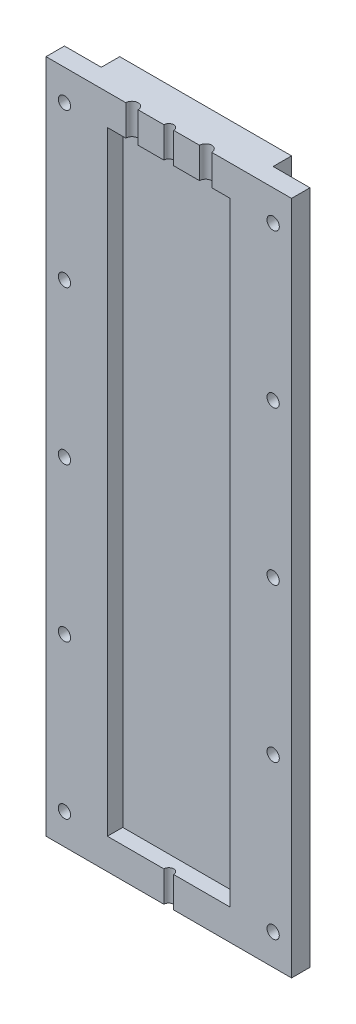
SolidWorks part; units mm, degrees
ref_plane "Front Plane" through (0, 0, 0) normal (0, 0, 1) x (1, 0, 0)
ref_plane "Top Plane" through (0, 0, 0) normal (0, 1, 0) x (1, 0, 0)
ref_plane "Right Plane" through (0, 0, 0) normal (1, 0, 0) x (0, 0, -1)
sketch "Sketch1" plane through (0, 0, 0) normal (0, 1, 0) x (1, 0, 0)
  line L1 (0, 0) -> (0, 6) construction
  line L6 (14, 0) -> (-14, 0)
  line L7 (14, 0) -> (14, 6)
  line L8 (14, 6) -> (-14, 6)
  line L9 (-14, 0) -> (-14, 6)
  dimension "D1" = 28
  dimension "D2" = 6
extrude "Boss-Extrude1" add sketch "Sketch1" along normal blind 105
sketch "Sketch2" plane through (0, 105, 0) normal (0, 1, 0) x (1, 0, 0)
  line L1 (-10, -2.5) -> (10, -2.5)
  line L2 (-10, -2.5) -> (-10, 2.5)
  line L3 (-10, 2.5) -> (10, 2.5)
  line L4 (10, -2.5) -> (10, 2.5)
  line L5 (-10, -2.5) -> (10, 2.5) construction
  line L6 (-10, 2.5) -> (10, -2.5) construction
  point P0 (0, 0)
  dimension "D1" = 5
  dimension "D2" = 20
extrude "Cut-Extrude1" cut sketch "Sketch2" against normal blind 100
sketch "Sketch3" plane through (0, 105, 0) normal (0, 1, 0) x (1, 0, 0)
  line L1 (14, 0) -> (20, 0)
  line L2 (14, 0) -> (14, 3)
  line L3 (14, 3) -> (20, 3)
  line L4 (20, 0) -> (20, 3)
  line L5 (0, 0) -> (0, 15) construction
  line L6 (-14, 3) -> (-20, 3)
  line L7 (-20, 0) -> (-20, 3)
  line L8 (-14, 0) -> (-20, 0)
  line L9 (-14, 0) -> (-14, 3)
  dimension "D1" = 3
  dimension "D2" = 6
extrude "Boss-Extrude2" add sketch "Sketch3" against normal blind 105
sketch "Sketch5" plane through (0, 105, 0) normal (0, 1, 0) x (1, 0, 0)
  line L0 (0, 0) -> (0, 6) construction
  line L1 (10, 0) -> (-10, 0) construction
  line L2 (14, 6) -> (-14, 6) construction
  circle A0 centre (10, 4) radius 1
  circle A1 centre (-10, 4) radius 1
  dimension "D1" = 2
  dimension "D2" = 10
  dimension "D3" = 2
extrude "Cut-Extrude3" [suppressed] cut sketch "Sketch5" against normal blind 10
sketch "Sketch6" plane through (0, 0, 0) normal (0, -1, 0) x (1, 0, 0)
  line L0 (-20, 0) -> (20, 0) construction
  circle A0 centre (0, 0) radius 0.8
  dimension "D1" = 1.6
extrude "Cut-Extrude4" cut sketch "Sketch6" against normal blind 10
sketch "Sketch8" plane through (0, 105, 0) normal (0, 1, 0) x (1, 0, 0)
  line L0 (-0.8, 0) -> (-10, 0)
  line L4 (10, 0) -> (0.8, 0)
  line L5 (-20, 3) -> (-20, 0)
  line L6 (-20, 0) -> (-10, 0)
  line L7 (-20, 3) -> (-14, 3)
  line L8 (-14, 3) -> (-14, 6)
  line L9 (-14, 6) -> (14, 6)
  line L10 (14, 6) -> (14, 3)
  line L11 (14, 3) -> (20, 3)
  line L12 (20, 3) -> (20, 0)
  line L13 (20, 0) -> (10, 0)
  line L17 (10, 0) -> (0.8, 0) construction
  arc A1 (-0.8, 0) -> (0.8, 0) centre (0, 0) cw
  dimension "D1" = 0.8
extrude "Boss-Extrude3" add sketch "Sketch8" along normal blind 5
sketch "Sketch7" plane through (0, 0, -3) normal (0, 0, -1) x (-1, 0, 0)
  line L0 (-17, 0) -> (-17, 110) construction
  line L1 (-20, 0) -> (-14, 0) construction
  line L3 (17, 110) -> (17, 0) construction
  line L5 (14, 0) -> (20, 0) construction
  line L6 (0, 0) -> (0, 105) construction
  line L7 (-20, 110) -> (-14, 110) construction
  line L8 (14, 110) -> (20, 110) construction
  circle A0 centre (-17, 5) radius 1
  circle A1 centre (-17, 30) radius 1
  circle A2 centre (-17, 55) radius 1
  circle A3 centre (-17, 80) radius 1
  circle A10 centre (17, 80) radius 1
  circle A11 centre (17, 55) radius 1
  circle A12 centre (17, 30) radius 1
  circle A13 centre (17, 5) radius 1
  circle A14 centre (-17, 105) radius 1
  circle A15 centre (17, 105) radius 1
  dimension "D1" = 2
  dimension "D2" = 5
  dimension "D4" = 25
  dimension "D3" = 5
extrude "Cut-Extrude5" cut sketch "Sketch7" against normal blind 10
sketch "Sketch9" plane through (0, 110, 0) normal (0, 1, 0) x (1, 0, 0)
  line L0 (0.8, 0) -> (20, 0) construction
  line L7 (0, 0) -> (0, 6) construction
  line L8 (14, 6) -> (-14, 6) construction
  circle A0 centre (6, 0) radius 1
  circle A1 centre (-6, 0) radius 1
  point P0 (6, 0)
  dimension "D1" = 2
  dimension "D3" = 6
extrude "Cut-Extrude6" cut sketch "Sketch9" against normal blind 5
